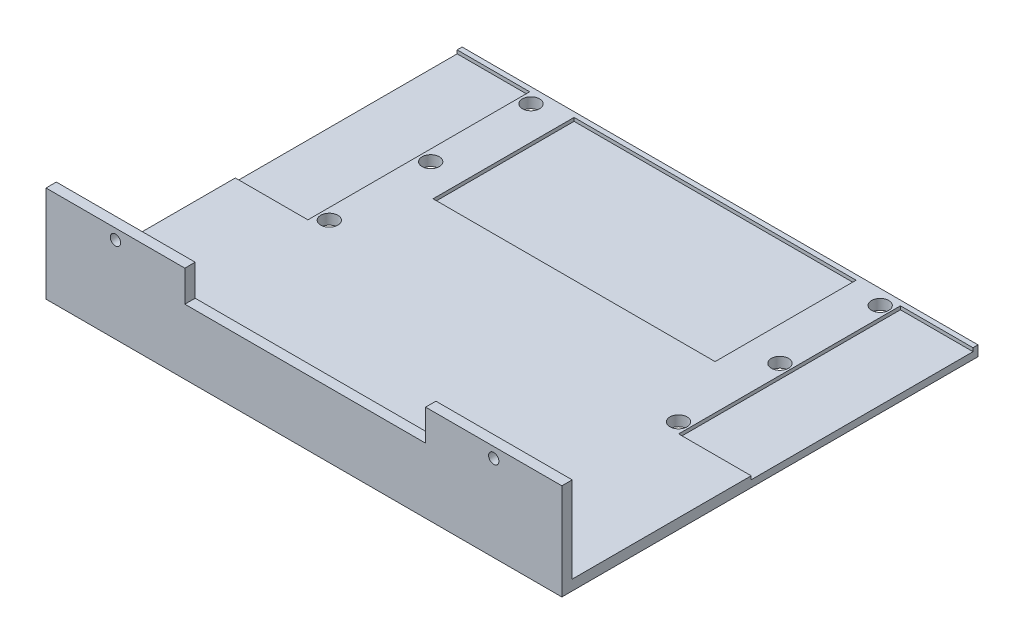
SolidWorks part; units mm, degrees
ref_plane "Front Plane" through (0, 0, 0) normal (0, 0, 1) x (1, 0, 0)
ref_plane "Top Plane" through (0, 0, 0) normal (0, 1, 0) x (1, 0, 0)
ref_plane "Right Plane" through (0, 0, 0) normal (1, 0, 0) x (0, 0, -1)
sketch "Sketch1" plane through (0, 0, 0) normal (1, 0, 0) x (0, 0, -1)
  line L0 (-70.2189, 2.934) -> (-70.2189, 30.934)
  line L1 (-70.2189, 30.934) -> (-67.2189, 30.934)
  line L2 (-70.2189, 2.934) -> (50.7811, 2.934)
  line L3 (-67.2189, 30.934) -> (-67.2189, 5.934)
  line L4 (-67.2189, 5.934) -> (50.7811, 5.934)
  line L5 (50.7811, 5.934) -> (50.7811, 2.934)
extrude "Boss-Extrude1" add sketch "Sketch1" against normal blind 150 contours L5 L2 L0 L1 L3 L4
sketch "Sketch2" plane through (0, 0, 70.2189) normal (0, 0, 1) x (1, 0, 0)
  line L0 (-150, 46.8899) -> (-109.626, 46.8899)
  line L1 (0.0546, 46.8899) -> (-39.9454, 46.8899)
  line L2 (-109.626, 30.934) -> (-109.626, 21.8563)
  line L3 (-150, 30.934) -> (0, 30.934) construction
  line L4 (-109.626, 21.8563) -> (-39.626, 21.8563)
  line L5 (-39.626, 21.8563) -> (-39.626, 30.934)
  line L6 (-39.626, 30.934) -> (-109.626, 30.934)
extrude "Cut-Extrude2" cut sketch "Sketch2" against normal blind 3 contours L6 L2 L4 L5
sketch "Sketch3" plane through (0, 5.934, 0) normal (0, 1, 0) x (1, 0, 0)
  line L0 (-21.1, 49.3311) -> (-21.1, -15.1689)
  line L2 (0, 49.3311) -> (-21.1, 49.3311)
  line L3 (0, -67.2189) -> (0, 50.7811) construction
  line L4 (-21.1, -15.1689) -> (0, -15.1689)
  line L5 (0, 49.3311) -> (0, -15.1689)
  line L6 (-150, 49.3311) -> (-150, -15.1689)
  line L7 (-150, -67.2189) -> (-150, 50.7811) construction
  line L8 (-150, -15.1689) -> (-128.9, -15.1689)
  line L9 (-128.9, -15.1689) -> (-128.9, 49.3311)
  line L10 (-128.9, 49.3311) -> (-150, 49.3311)
extrude "Cut-Extrude3" cut sketch "Sketch3" against normal blind 1
sketch "Sketch4" plane through (0, 5.934, 0) normal (0, 1, 0) x (1, 0, 0)
  line L0 (-116, 49.3311) -> (-116, 8.3311)
  line L1 (-116, 8.3311) -> (-34, 8.3311)
  line L2 (-116, 49.3311) -> (-34, 49.3311)
  line L3 (-34, 8.3311) -> (-34, 49.3311)
extrude "Cut-Extrude4" cut sketch "Sketch4" against normal blind 1
sketch "Sketch5" plane through (0, 5.934, 0) normal (0, 1, 0) x (1, 0, 0)
  circle A0 centre (-24.1434, -12.1483) radius 2.5
  circle A1 centre (-24.1434, 46.4825) radius 2.5
  circle A2 centre (-24.1434, 17.329) radius 2.5
  circle A3 centre (-125.6946, 46.4825) radius 2.5
  circle A4 centre (-125.6946, 17.329) radius 2.5
  circle A5 centre (-125.6946, -12.1483) radius 2.5
extrude "Cut-Extrude5" cut sketch "Sketch5" against normal blind 3
sketch "Sketch6" plane through (0, 0, 70.2189) normal (0, 0, 1) x (1, 0, 0)
  circle A0 centre (-129.813, 27.934) radius 1.5
  circle A1 centre (-19.813, 27.934) radius 1.5
extrude "Cut-Extrude6" cut sketch "Sketch6" against normal blind 3
